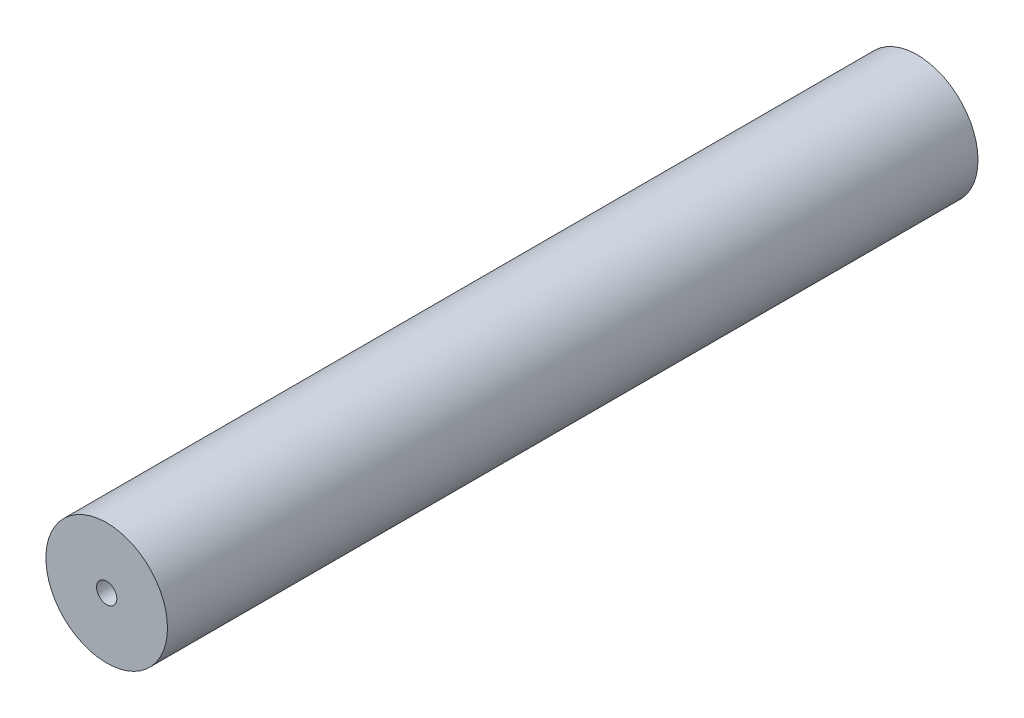
SolidWorks part; units mm, degrees
ref_plane "Front Plane" through (0, 0, 0) normal (0, 0, 1) x (1, 0, 0)
ref_plane "Top Plane" through (0, 0, 0) normal (0, 1, 0) x (1, 0, 0)
ref_plane "Right Plane" through (0, 0, 0) normal (1, 0, 0) x (0, 0, -1)
sketch "Sketch1" plane through (0, 0, 0) normal (0, 0, 1) x (1, 0, 0)
  circle A0 centre (0, 0) radius 38.1
  circle A1 centre (0, 0) radius 6.35
  dimension "D1" = 76.2
  dimension "D2" = 12.7
extrude "Boss-Extrude1" add sketch "Sketch1" along normal blind 508
equation "\"Thick\"= \"in\""
